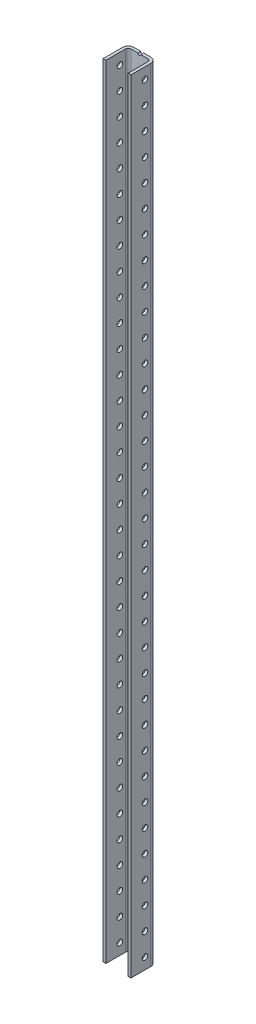
SolidWorks part; units mm, degrees
ref_plane "Front Plane" through (0, 0, 0) normal (0, 0, 1) x (1, 0, 0)
ref_plane "Top Plane" through (0, 0, 0) normal (0, 1, 0) x (1, 0, 0)
ref_plane "Right Plane" through (0, 0, 0) normal (1, 0, 0) x (0, 0, -1)
sketch "Sketch2" plane through (0, 0, 0) normal (0, 1, 0) x (1, 0, 0)
  line L0 (-12.7, 0) -> (12.7, 0) construction
  line L1 (-12.7, 0) -> (-12.7, 22.225)
  line L2 (-9.525, 25.4) -> (9.525, 25.4)
  line L3 (12.7, 22.225) -> (12.7, 0)
  line L4 (-15.875, 0) -> (-15.875, 22.225)
  line L5 (-9.525, 28.575) -> (9.525, 28.575)
  line L6 (15.875, 22.225) -> (15.875, 0)
  line L7 (-15.875, 0) -> (-12.7, 0)
  line L8 (12.7, 0) -> (15.875, 0)
  line L9 (-12.7, 25.4) -> (12.7, 25.4) construction
  line L10 (12.7, 25.4) -> (12.7, 0) construction
  line L11 (-12.7, 0) -> (-12.7, 25.4) construction
  line L12 (-15.875, 28.575) -> (15.875, 28.575) construction
  line L13 (15.875, 28.575) -> (15.875, 0) construction
  line L14 (-15.875, 0) -> (-15.875, 28.575) construction
  arc A0 (9.525, 25.4) -> (12.7, 22.225) centre (9.525, 22.225) cw
  arc A1 (-12.7, 22.225) -> (-9.525, 25.4) centre (-9.525, 22.225) cw
  arc A2 (9.525, 28.575) -> (15.875, 22.225) centre (9.525, 22.225) cw
  arc A3 (-15.875, 22.225) -> (-9.525, 28.575) centre (-9.525, 22.225) cw
  dimension "D4" = 3.175
  dimension "D5" = 6.35
  dimension "D1" = 25.4
  dimension "D2" = 25.4
  dimension "D3" = 3.175
extrude "Boss-Extrude1" add sketch "Sketch2" along normal mid plane 889
sketch "Sketch3" plane through (0, 0, -28.575) normal (0, 0, -1) x (-1, 0, 0)
  line L0 (0, 444.5) -> (0, -444.5) construction
  line L1 (-9.525, 444.5) -> (9.525, 444.5) construction
  line L2 (-9.525, -444.5) -> (9.525, -444.5) construction
  line L3 (-2.032, 444.5) -> (-2.032, -444.5) construction
  circle A0 centre (0, 444.5) radius 1.651
  circle A1 centre (-2.032, 361.95) radius 4.826
  circle A2 centre (-2.032, 336.55) radius 4.826
  circle A3 centre (-2.032, 107.95) radius 4.826
  circle A4 centre (-2.032, 82.55) radius 4.826
  circle A5 centre (-2.032, -107.95) radius 4.826
  circle A6 centre (-2.032, -82.55) radius 4.826
  circle A7 centre (0, -241.3) radius 1.5875
  circle A8 centre (2.032, 0) radius 4.826
  circle A9 centre (-2.032, -336.55) radius 4.826
  circle A10 centre (-2.032, -361.95) radius 4.826
  dimension "D1" = 3.302
  dimension "D3" = 9.652
  dimension "D12" = 3.175
  dimension "D14" = 9.652
  dimension "D2" = 2.032
  dimension "D4" = 82.55
  dimension "D5" = 25.4
  dimension "D6" = 254
  dimension "D7" = 25.4
  dimension "D8" = 25.4
  dimension "D9" = 25.4
  dimension "D10" = 82.55
  dimension "D11" = 95.25
  dimension "D13" = 228.6
  dimension "D15" = 2.032
  dimension "D16" = 444.5
extrude "Cut-Extrude1" cut sketch "Sketch3" against normal through all
sketch "Sketch4" plane through (15.875, 0, 0) normal (1, 0, 0) x (0, 0, -1)
  line L0 (28.575, 444.5) -> (28.575, -444.5) construction
  line L1 (0, 444.5) -> (22.225, 444.5) construction
  circle A0 centre (15.875, 431.8) radius 3.175
  dimension "D2" = 6.35
  dimension "D1" = 12.7
  dimension "D3" = 12.7
extrude "Cut-Extrude2" cut sketch "Sketch4" against normal through all
pattern_linear "LPattern1" count 35 spacing 25.4 along (0, -1, 0) of "Cut-Extrude2"
